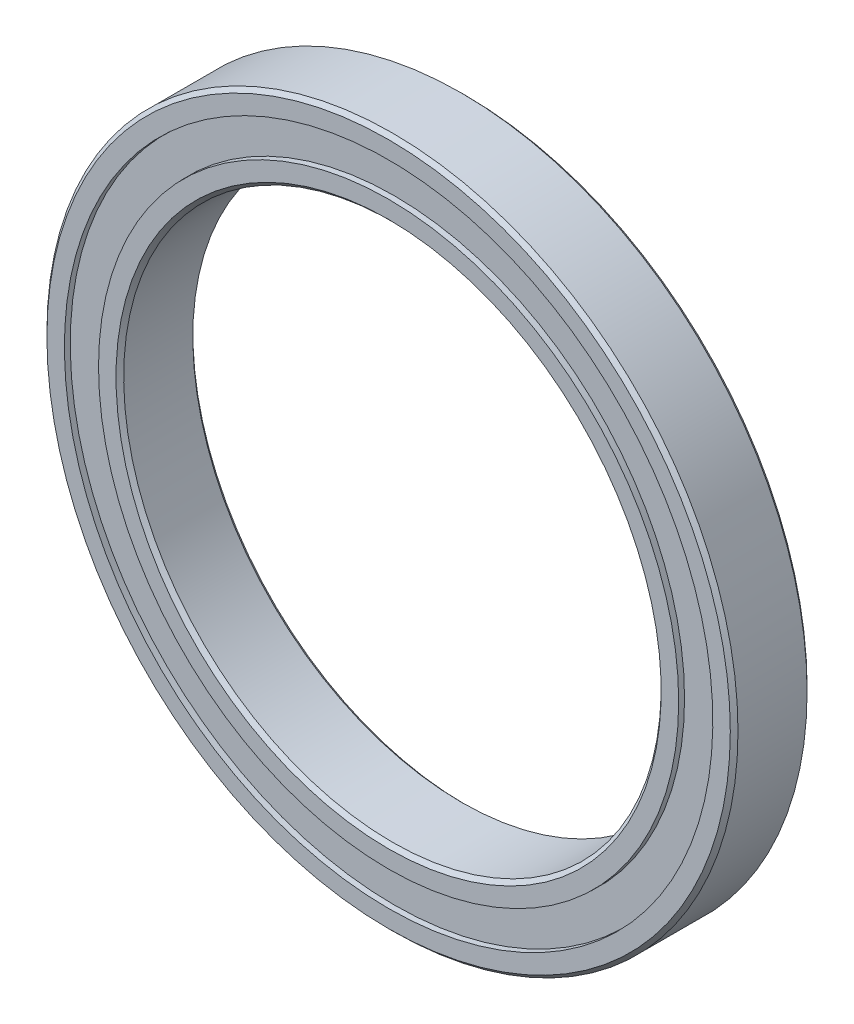
SolidWorks part; units mm, degrees
ref_plane "Front Plane" through (0, 0, 0) normal (0, 0, 1) x (1, 0, 0)
ref_plane "Top Plane" through (0, 0, 0) normal (0, 1, 0) x (1, 0, 0)
ref_plane "Right Plane" through (0, 0, 0) normal (1, 0, 0) x (0, 0, -1)
sketch "Sketch1" plane through (0, 0, 0) normal (0, 0, 1) x (1, 0, 0)
  circle A0 centre (0, 0) radius 45
  circle A1 centre (0, 0) radius 35
  dimension "OD" = 90
  dimension "ID" = 70
  dimension "For Shaft Diameter" = 70
  dimension "For Housing ID" = 90
sketch "Sketch8" plane through (0, 0, 0) normal (1, 0, 0) x (0, 0, -1)
  line L1 (-5, 45) -> (5, 45)
  line L2 (-5, 45) -> (-5, -45)
  line L3 (-5, -45) -> (5, -45)
  line L4 (5, 45) -> (5, -45)
  line L5 (-5, 45) -> (5, -45) construction
  line L6 (-5, -45) -> (5, 45) construction
  point P0 (0, 0)
  point P6 (0, -45)
  dimension "Width" = 10
sketch "Sketch5" plane through (0, 0, 0) normal (1, 0, 0) x (0, 0, -1)
  line L0 (-5, 0) -> (5, 0) construction
  line L1 (0, 45) -> (0, -45) construction
  line L2 (4.5, 45) -> (-4.5, 45)
  line L3 (-4.5, 45) -> (-5, 44.5)
  line L4 (-5, 44.5) -> (-5, 42.2222)
  line L5 (-5, 42.2222) -> (-2.2222, 42.2222)
  line L6 (5, 42.2222) -> (2.2222, 42.2222)
  line L7 (5, 44.5) -> (5, 42.2222)
  line L8 (4.5, 45) -> (5, 44.5)
  line L9 (0, 45) -> (0, 40) construction
  line L10 (0, 40) -> (0, 35) construction
  line L11 (-3.1427, 40) -> (-5, 40) construction
  line L12 (3.8808, 37.8032) -> (4.2618, 37.8032)
  line L13 (-3.8808, 37.8032) -> (-4.2618, 37.8032)
  line L14 (-3.8808, 37.8032) -> (-3.8808, 42.1968)
  line L15 (-3.8808, 42.1968) -> (-4.2618, 42.1968)
  line L16 (-4.2618, 37.8032) -> (-4.2618, 42.1968)
  line L17 (-3.8808, 37.8032) -> (-4.2618, 42.1968) construction
  line L18 (-3.8808, 42.1968) -> (-4.2618, 37.8032) construction
  line L19 (4.2618, 37.8032) -> (4.2618, 42.1968)
  line L20 (3.8808, 42.1968) -> (4.2618, 42.1968)
  line L21 (3.8808, 37.8032) -> (3.8808, 42.1968)
  line L22 (0, 45) -> (0, -45) construction
  line L23 (5, 0) -> (5, 45) construction
  line L24 (5, 45) -> (4.5, 45) construction
  line L25 (-5, 0) -> (-5, 45) construction
  line L26 (-5, 45) -> (-4.5, 45) construction
  line L27 (5, 0) -> (5, -45) construction
  line L28 (-5, 0) -> (-5, -45) construction
  line L29 (-5, -45) -> (5, -45) construction
  arc A0 (-2.2222, 42.2222) -> (2.2222, 42.2222) centre (0, 40) cw
  circle A1 centre (0, 40) radius 3.1427 construction
  point P14 (0, 35)
  point P15 (-4.0713, 40)
  dimension "D1" = 45
  dimension "D2" = 0.5
  dimension "D3" = 4.4444
  dimension "D4" = 2.2222
  dimension "D5" = 0.381
  dimension "D6" = 0.0254
revolve "Revolve1" add sketch "Sketch5" angle 360 about L0
sketch "Sketch3" plane through (0, 0, 0) normal (1, 0, 0) x (0, 0, -1)
  line L0 (-5, 37.7778) -> (-2.2222, 37.7778)
  line L1 (0, 45) -> (0, -45) construction
  line L2 (-5, 44.5) -> (-5, 42.2222) construction
  line L3 (-5, 37.7778) -> (-5, 35.5)
  line L4 (-4.5, 45) -> (-5, 44.5) construction
  line L5 (-5, 35.5) -> (-4.5, 35)
  line L6 (-4.5, 35) -> (4.5, 35)
  line L7 (4.5, 45) -> (4.5, -45) construction
  line L8 (4.5, 35) -> (5, 35.5)
  line L9 (5, -44.5) -> (5, 44.5) construction
  line L10 (5, 35.5) -> (5, 37.7778)
  line L11 (5, 37.7778) -> (2.2222, 37.7778)
  line L13 (4.5, 45) -> (5, 44.5) construction
  arc A0 (2.2222, 42.2222) -> (-2.2222, 42.2222) centre (0, 40) ccw construction
  arc A1 (2.2222, 37.7778) -> (-2.2222, 37.7778) centre (0, 40) cw
revolve "Revolve3" add sketch "Sketch3" angle 360 about L0
sketch "Sketch4" plane through (0, 0, 0) normal (1, 0, 0) x (0, 0, -1)
  line L0 (-3.1427, 40) -> (3.1427, 40)
  arc A2 (-3.1427, 40) -> (3.1427, 40) centre (0, 40) cw
  arc A3 (2.2222, 42.2222) -> (-2.2222, 42.2222) centre (0, 40) ccw construction
revolve "Revolve4" add sketch "Sketch4" angle 360 about L0
pattern_circular "CirPattern1" count 24 every 15 about axis through (0, 0, 0) along (0, 0, 1) of bodies 104
equation "\"D2@Sketch5\" = \"Width@Sketch8\" * .05"
equation "\"D3@Sketch5\" = \"Width@Sketch8\" / 2.25"
equation "\"D4@Sketch5\"=((\"OD@Sketch1\"-\"ID@Sketch1\")/2)/4.5"
equation "\"D2@CirPattern1\" = 360/\"Balls@CirPattern1\""
